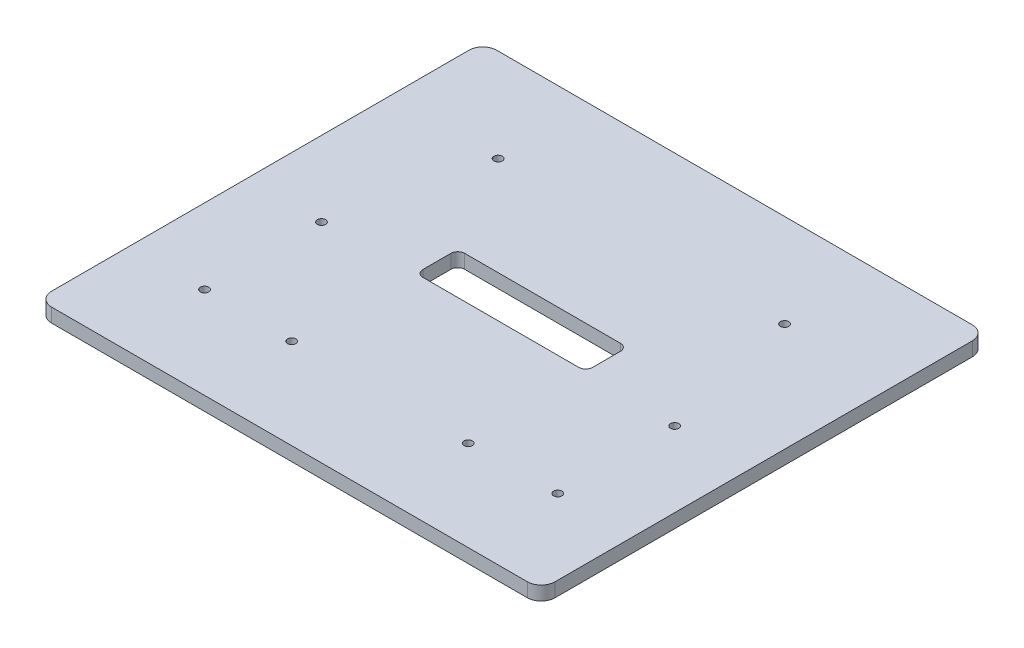
SolidWorks part; units mm, degrees
material "Acrílico (médio-alto impacto)"
ref_plane "Plano frontal" through (0, 0, 0) normal (0, 0, 1) x (1, 0, 0)
ref_plane "Plano superior" through (0, 0, 0) normal (0, 1, 0) x (1, 0, 0)
ref_plane "Plano direito" through (0, 0, 0) normal (1, 0, 0) x (0, 0, -1)
sketch "Esboço1" plane through (0, 0, 0) normal (0, 1, 0) x (1, 0, 0)
  line L1 (-61.8658, 131.6616) -> (109.1342, 131.6616)
  line L2 (-66.8658, 126.6616) -> (-66.8658, -23.3384)
  line L3 (-61.8658, -28.3384) -> (109.1342, -28.3384)
  line L4 (114.1342, 126.6616) -> (114.1342, -23.3384)
  arc A0 (109.1342, 131.6616) -> (114.1342, 126.6616) centre (109.1342, 126.6616) cw
  arc A1 (109.1342, -28.3384) -> (114.1342, -23.3384) centre (109.1342, -23.3384) ccw
  arc A2 (-61.8658, -28.3384) -> (-66.8658, -23.3384) centre (-61.8658, -23.3384) cw
  arc A3 (-61.8658, 131.6616) -> (-66.8658, 126.6616) centre (-61.8658, 126.6616) ccw
  dimension "D1" = 5
extrude "Ressalto-extrusão1" add sketch "Esboço1" along normal blind 5
sketch "Esboço2" plane through (0, 5, 0) normal (0, 1, 0) x (1, 0, 0)
  line L0 (-66.8658, 126.6616) -> (-66.8658, -23.3384) construction
  line L1 (-32.8658, 113.1616) -> (80.1342, 113.1616) construction
  line L2 (-37.8658, 108.1616) -> (-37.8658, -4.8384) construction
  line L3 (-32.8658, -9.8384) -> (80.1342, -9.8384) construction
  line L4 (85.1342, 108.1616) -> (85.1342, -4.8384) construction
  line L6 (114.1342, -23.3384) -> (114.1342, 126.6616) construction
  line L7 (109.1342, 131.6616) -> (-61.8658, 131.6616) construction
  line L9 (-61.8658, -28.3384) -> (109.1342, -28.3384) construction
  circle A0 centre (-27.8658, 98.1616) radius 1.5
  circle A1 centre (75.1342, 98.1616) radius 1.5
  circle A2 centre (-8.1158, 4.1616) radius 1.5
  circle A3 centre (55.3842, 4.1616) radius 1.5
  arc A4 (85.1342, -4.8384) -> (80.1342, -9.8384) centre (80.1342, -4.8384) cw construction
  arc A5 (-32.8658, -9.8384) -> (-37.8658, -4.8384) centre (-32.8658, -4.8384) cw construction
  arc A6 (85.1342, 108.1616) -> (80.1342, 113.1616) centre (80.1342, 108.1616) ccw construction
  arc A7 (-32.8658, 113.1616) -> (-37.8658, 108.1616) centre (-32.8658, 108.1616) ccw construction
  dimension "D5" = 15
  dimension "D7" = 15
  dimension "D8" = 10
  dimension "D9" = 29.75
  dimension "D11" = 29.75
  dimension "D12" = 5
  dimension "D13" = 14
  dimension "D1" = 29
  dimension "D2" = 29
  dimension "D3" = 18.5
  dimension "D4" = 18.5
  dimension "D6" = 10
  dimension "D10" = 14
extrude "Corte-extrusão1" cut sketch "Esboço2" against normal blind 5
sketch "Esboço3" plane through (0, 5, 0) normal (0, 1, 0) x (1, 0, 0)
  line L0 (109.1342, 131.6616) -> (-61.8658, 131.6616) construction
  line L1 (-66.8658, 126.6616) -> (-66.8658, -23.3384) construction
  line L2 (114.1342, -23.3384) -> (114.1342, 126.6616) construction
  circle A0 centre (-39.8658, 46.6616) radius 1.5
  circle A1 centre (-39.8658, 4.6116) radius 1.5
  circle A2 centre (87.1342, 46.6616) radius 1.5
  circle A3 centre (87.1342, 4.6116) radius 1.5
  dimension "D1" = 42.05
  dimension "D2" = 85
  dimension "D3" = 27
  dimension "D4" = 27
  dimension "D5" = 3
  dimension "D6" = 3
  dimension "D7" = 27
  dimension "D8" = 85
  dimension "D9" = 27
  dimension "D10" = 42.05
extrude "Corte-extrusão2" cut sketch "Esboço3" against normal blind 10
sketch "Esboço4" plane through (0, 5, 0) normal (0, 1, 0) x (1, 0, 0)
  line L0 (-66.8658, 126.6616) -> (-66.8658, -23.3384) construction
  line L1 (-4.3658, 62.6616) -> (51.6342, 62.6616)
  line L2 (-6.8658, 60.1616) -> (-6.8658, 50.1616)
  line L3 (-4.3658, 47.6616) -> (51.6342, 47.6616)
  line L4 (54.1342, 60.1616) -> (54.1342, 50.1616)
  line L5 (114.1342, -23.3384) -> (114.1342, 126.6616) construction
  line L6 (-61.8658, -28.3384) -> (109.1342, -28.3384) construction
  line L7 (109.1342, 131.6616) -> (-61.8658, 131.6616) construction
  arc A0 (54.1342, 60.1616) -> (51.6342, 62.6616) centre (51.6342, 60.1616) ccw
  arc A1 (54.1342, 50.1616) -> (51.6342, 47.6616) centre (51.6342, 50.1616) cw
  arc A2 (-4.3658, 47.6616) -> (-6.8658, 50.1616) centre (-4.3658, 50.1616) cw
  arc A3 (-4.3658, 62.6616) -> (-6.8658, 60.1616) centre (-4.3658, 60.1616) ccw
  dimension "D4" = 2.5
  dimension "D1" = 60
  dimension "D2" = 60
  dimension "D3" = 76
  dimension "D5" = 69
extrude "Corte-extrusão3" cut sketch "Esboço4" against normal blind 10
